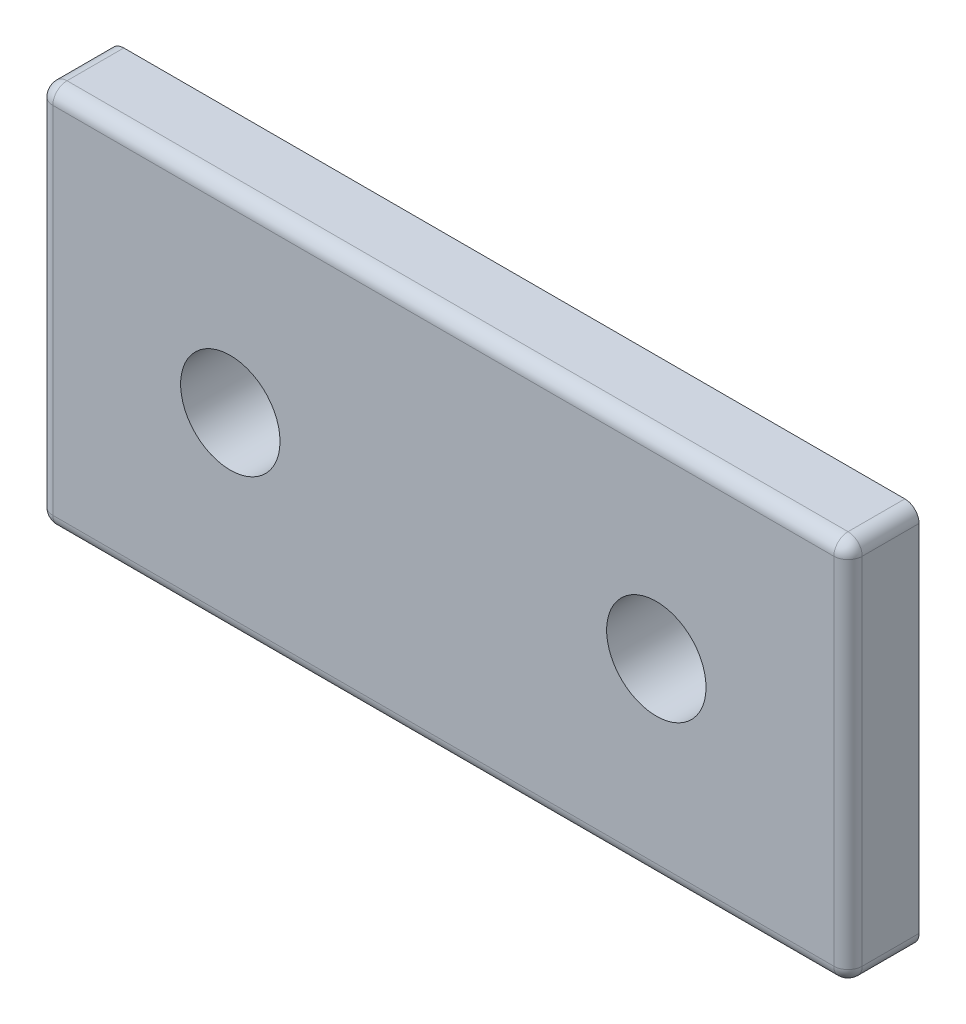
SolidWorks part; units mm, degrees
ref_plane "Front Plane" through (0, 0, 0) normal (0, 0, 1) x (1, 0, 0)
ref_plane "Top Plane" through (0, 0, 0) normal (0, 1, 0) x (1, 0, 0)
ref_plane "Right Plane" through (0, 0, 0) normal (1, 0, 0) x (0, 0, -1)
sketch "Sketch1" plane through (0, 0, 0) normal (0, 0, 1) x (1, 0, 0)
  line L0 (0, 0) -> (0, 27)
  line L1 (13.5, 13.5) -> (43.5, 13.5) construction
  line L4 (57, 27) -> (0, 27)
  line L5 (57, 0) -> (0, 0)
  line L7 (57, 27) -> (57, 0)
  circle A0 centre (13.5, 13.5) radius 3.5
  circle A1 centre (43.5, 13.5) radius 3.5
  dimension "D1" = 30
  dimension "E" = 7
  dimension "D2" = 13.5
  dimension "C" = 27
  dimension "D3" = 13.5
  dimension "B" = 57
extrude "Boss-Extrude1" add sketch "Sketch1" along normal mid plane 5
fillet "Fillet1" radius 1 8 edges at (0, 0, 0) (0, 13.5, 2.5) (28.5, 0, 2.5) (57, 13.5, 2.5) (57, 0, 0) (57, 27, 0) (28.5, 27, 2.5) (0, 27, 0)
